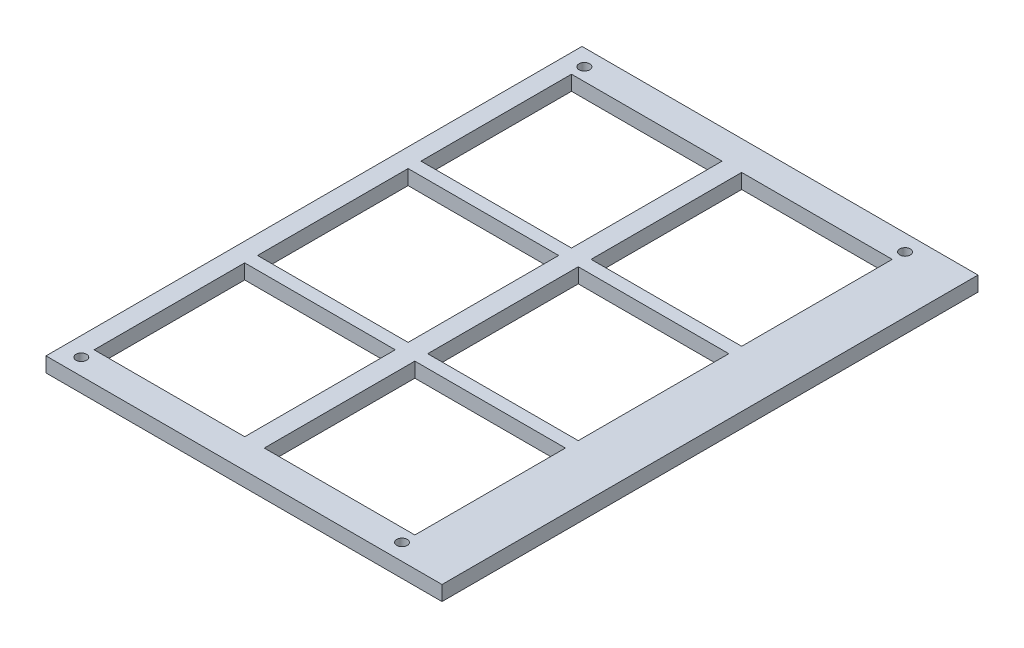
SolidWorks part; units mm, degrees
ref_plane "前视" through (0, 0, 0) normal (0, 0, 1) x (1, 0, 0)
ref_plane "上视" through (0, 0, 0) normal (0, 1, 0) x (1, 0, 0)
ref_plane "右视" through (0, 0, 0) normal (1, 0, 0) x (0, 0, -1)
sketch "Sketch1" plane through (0, 0, 0) normal (0, 1, 0) x (1, 0, 0)
  line L1 (-133.61, 180.84) -> (133.61, 180.84)
  line L2 (-133.61, 180.84) -> (-133.61, -180.84)
  line L3 (-133.61, -180.84) -> (133.61, -180.84)
  line L4 (133.61, 180.84) -> (133.61, -180.84)
  circle A0 centre (-120.91, -169.7275) radius 3.57
  circle A1 centre (-120.91, 169.7275) radius 3.57
  circle A2 centre (95.51, 169.7275) radius 3.57
  circle A3 centre (95.51, -169.7275) radius 3.57
  point P4 (-120.91, -169.7275)
  point P7 (95.51, -169.7275)
  point P8 (95.51, 169.7275)
  point P9 (-120.91, 169.7275)
  dimension "D5" = 38.1
  dimension "D7" = 216.42
  dimension "D1" = 267.22
  dimension "D2" = 361.68
  dimension "D3" = 11.1125
  dimension "D4" = 12.7
  dimension "D6" = 11.1125
  dimension "D8" = 38.1
  dimension "D9" = 11.1125
  dimension "D10" = 12.7
  dimension "D11" = 180.84
  dimension "D12" = 133.61
extrude "Boss-Extrude1" add sketch "Sketch1" along normal blind 10
sketch "Sketch2" plane through (0, 10, 0) normal (0, 1, 0) x (1, 0, 0)
  line L0 (-120.91, 50.8) -> (-19.31, 50.8)
  line L1 (-120.91, 50.8) -> (-120.91, -50.8)
  line L2 (-19.31, 50.8) -> (-19.31, -50.8)
  line L3 (-120.91, -50.8) -> (-19.31, -50.8)
  line L4 (-120.91, 50.8) -> (-19.31, -50.8) construction
  line L5 (-19.31, 50.8) -> (-120.91, -50.8) construction
  circle A1 centre (-120.91, 169.7275) radius 3.57 construction
  point P1 (-70.11, 0)
  dimension "D4" = 0
  dimension "D3" = 50.8
  dimension "D1" = 101.6
  dimension "D2" = 101.6
extrude "Cut-Extrude1" cut sketch "Sketch2" against normal through all
pattern_linear "LPattern1" count 2 spacing 110.265 along (0, 0, -1) of "Cut-Extrude1"
pattern_linear "LPattern2" count 2 spacing 110.265 along (0, 0, 1) of "Cut-Extrude1"
pattern_linear "LPattern3" count 2 spacing 114.82 along (1, 0, 0) of "Cut-Extrude1", "LPattern1", "LPattern2"
